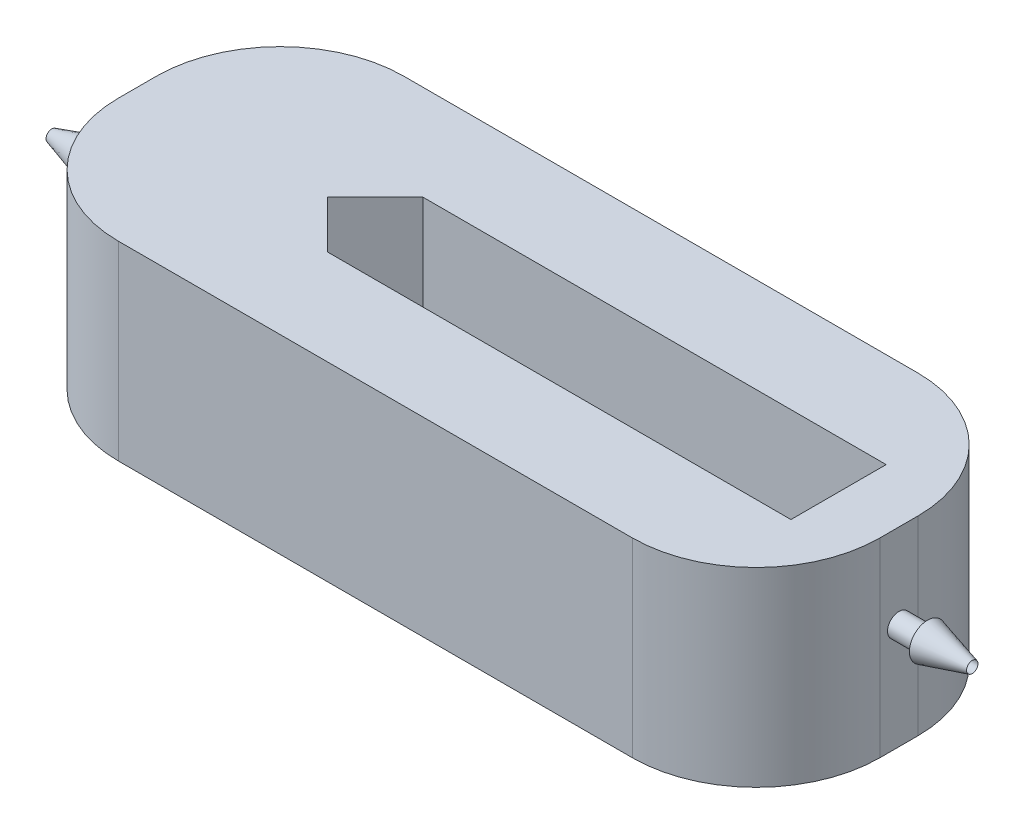
SolidWorks part; units mm, degrees
ref_plane "Front Plane" through (0, 0, 0) normal (0, 0, 1) x (1, 0, 0)
ref_plane "Top Plane" through (0, 0, 0) normal (0, 1, 0) x (1, 0, 0)
ref_plane "Right Plane" through (0, 0, 0) normal (1, 0, 0) x (0, 0, -1)
sketch "Sketch1" plane through (0, 0, 0) normal (0, 1, 0) x (1, 0, 0)
  line L1 (-40, -15) -> (40, -15)
  line L2 (-40, -15) -> (-40, 15)
  line L3 (-40, 15) -> (40, 15)
  line L4 (40, -15) -> (40, 15)
  line L5 (-40, -15) -> (40, 15) construction
  line L6 (-40, 15) -> (40, -15) construction
  point P0 (0, 0)
  point P5 (0, 0)
  dimension "D1" = 30
  dimension "D2" = 80
extrude "Boss-Extrude1" add sketch "Sketch1" along normal blind 60
sketch "Sketch2" plane through (0, 60, 0) normal (0, 1, 0) x (1, 0, 0)
  line L0 (-15, 5) -> (15, 5)
  line L3 (15, -5) -> (-15, -5)
  line L4 (-15, -5) -> (-20, 0)
  line L5 (-20, 0) -> (-15, 5)
  line L6 (15, 5) -> (33.657, 5)
  line L7 (33.657, 5) -> (33.657, -5)
  line L8 (33.657, -5) -> (15, -5)
  dimension "D1" = 15
  dimension "D2" = 15
  dimension "D3" = 15
  dimension "D4" = 15
  dimension "D5" = 5
  dimension "D6" = 5
extrude "Cut-Extrude1" cut sketch "Sketch2" against normal blind 75
sketch "Sketch3" plane through (-40, 0, 0) normal (-1, 0, 0) x (0, 0, 1)
  circle A0 centre (0, 51.112) radius 0.8
  dimension "D1" = 1.6
extrude "Cut-Extrude2" cut sketch "Sketch3" against normal through all and the other way through all
sketch "Sketch4" plane through (-40, 0, 0) normal (-1, 0, 0) x (0, 0, 1)
  circle A0 centre (0, 51.112) radius 1.5
  circle A1 centre (0, 51.112) radius 1.2
  dimension "D1" = 2.4
  dimension "D2" = 3
extrude "Boss-Extrude2" add sketch "Sketch4" along normal blind 3
sketch "Sketch6" plane through (0, 0, 0) normal (0, 0, 1) x (1, 0, 0)
  line L0 (-43, 51.112) -> (-49.3252, 51.112)
  line L1 (-43, 52.612) -> (-43, 49.612) construction
  line L2 (-43, 51.112) -> (-43, 53.512)
  line L3 (-43, 53.512) -> (-49.3252, 51.612)
  line L4 (-49.3252, 51.612) -> (-49.3252, 51.112)
  dimension "D1" = 2.4
  dimension "D2" = 0.5
revolve "Revolve1" add sketch "Sketch6" angle 360 about L0
sketch "Sketch7" plane through (-49.3252, 0, 0) normal (-1, 0, 0) x (0, 0, 1)
  circle A0 centre (0, 51.112) radius 0.6
  dimension "D1" = 1.2
extrude "Cut-Extrude3" cut sketch "Sketch7" against normal blind 2
sketch "Sketch8" plane through (-47.3252, 0, 0) normal (-1, 0, 0) x (0, 0, 1)
  circle A0 centre (0, 51.112) radius 0.8
  dimension "D1" = 1.6
extrude "Cut-Extrude4" cut sketch "Sketch8" against normal blind 53
fillet "Fillet1" radius 13 4 edges at (40, 30, -15) (-40, 30, -15) (40, 30, 15) (-40, 30, 15)
sketch "Sketch9" plane through (40, 0, 0) normal (1, 0, 0) x (0, 0, -1)
  circle A0 centre (0, 51.112) radius 0.8
  circle A1 centre (0, 51.112) radius 1.2
  dimension "D1" = 2.4
extrude "Boss-Extrude3" add sketch "Sketch9" along normal blind 3
sketch "Sketch11" plane through (0, 0, 0) normal (0, 0, 1) x (1, 0, 0)
  line L0 (43, 51.112) -> (43, 53.0133)
  line L1 (43, 49.912) -> (43, 52.312) construction
  line L2 (43, 51.112) -> (47.7051, 51.112)
  line L3 (47.7051, 51.112) -> (47.7051, 51.712)
  line L4 (47.7051, 51.712) -> (43, 53.0133)
  dimension "D1" = 0.6
  dimension "D2" = 1.9014
  dimension "D3" = 4.7051
revolve "Revolve2" add sketch "Sketch11" angle 360 about L2
sketch "Sketch12" plane through (47.7051, 0, 0) normal (1, 0, 0) x (0, 0, -1)
  circle A0 centre (0, 51.112) radius 0.6
extrude "Cut-Extrude5" cut sketch "Sketch12" against normal blind 2
sketch "Sketch14" plane through (45.7051, 0, 0) normal (1, 0, 0) x (0, 0, -1)
  circle A0 centre (0, 51.112) radius 0.8
extrude "Cut-Extrude6" cut sketch "Sketch14" against normal blind 35
ref_plane "Plane2" through (0, -10, 0) normal (0, -1, 0) x (-1, 0, 0)
sketch "Sketch15" plane through (0, -10, 0) normal (0, -1, 0) x (-1, 0, 0)
  line L1 (-41.9055, 15.8797) -> (41.7906, 15.8797)
  line L2 (-41.9055, 15.8797) -> (-41.9055, -15.8187)
  line L3 (-41.9055, -15.8187) -> (41.7906, -15.8187)
  line L4 (41.7906, 15.8797) -> (41.7906, -15.8187)
extrude "Cut-Extrude7" cut sketch "Sketch15" against normal blind 50
